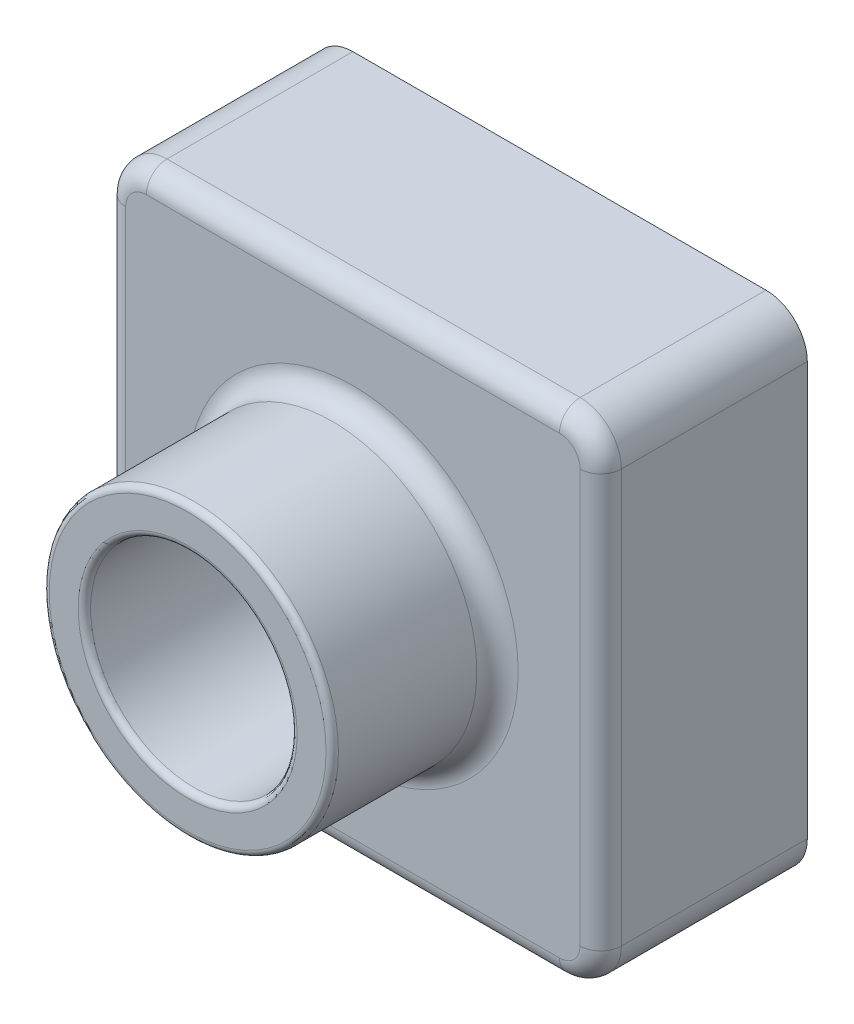
SolidWorks part; units mm, degrees
ref_plane "Front" through (0, 0, 0) normal (0, 0, 1) x (1, 0, 0)
ref_plane "Top" through (0, 0, 0) normal (0, 1, 0) x (1, 0, 0)
ref_plane "Right" through (0, 0, 0) normal (1, 0, 0) x (0, 0, -1)
sketch "Sketch4" plane through (0, 0, 0) normal (0, 0, 1) x (1, 0, 0)
  line L1 (0, 0) -> (120, 0)
  line L2 (0, 0) -> (0, 120)
  line L3 (0, 120) -> (120, 120)
  line L4 (120, 0) -> (120, 120)
  line L5 (0, 0) -> (120, 120) construction
  line L6 (0, 120) -> (120, 0) construction
  point P5 (60, 60)
  dimension "D1" = 120
  dimension "D2" = 120
extrude "Boss-Extrude2" add sketch "Sketch4" along normal blind 50
sketch "Sketch5" plane through (0, 0, 50) normal (0, 0, 1) x (1, 0, 0)
  line L0 (120, 120) -> (0, 120) construction
  line L3 (120, 0) -> (120, 120) construction
  circle A0 centre (60, 60) radius 35
  dimension "D1" = 70
  dimension "D3" = 60
  dimension "D2" = 60
extrude "Boss-Extrude3" add sketch "Sketch5" along normal blind 40
sketch "Sketch6" plane through (0, 0, 90) normal (0, 0, 1) x (1, 0, 0)
  circle A0 centre (60, 60) radius 25
  dimension "D1" = 50
extrude "Cut-Extrude1" cut sketch "Sketch6" against normal through all
fillet "Fillet1" radius 10 4 edges at (0, 120, 25) (0, 0, 25) (120, 0, 25) (120, 120, 25)
fillet "Fillet2" radius 1.5 2 edges at (95, 60, 90) (85, 60, 90)
fillet "Fillet3" radius 5 9 edges at (117.0711, 117.0711, 50) (120, 60, 50) (117.0711, 2.9289, 50) (60, 0, 50) (2.9289, 2.9289, 50) (0, 60, 50) (2.9289, 117.0711, 50) (60, 120, 50) (95, 60, 50)
shell "Shell1" thickness 2
